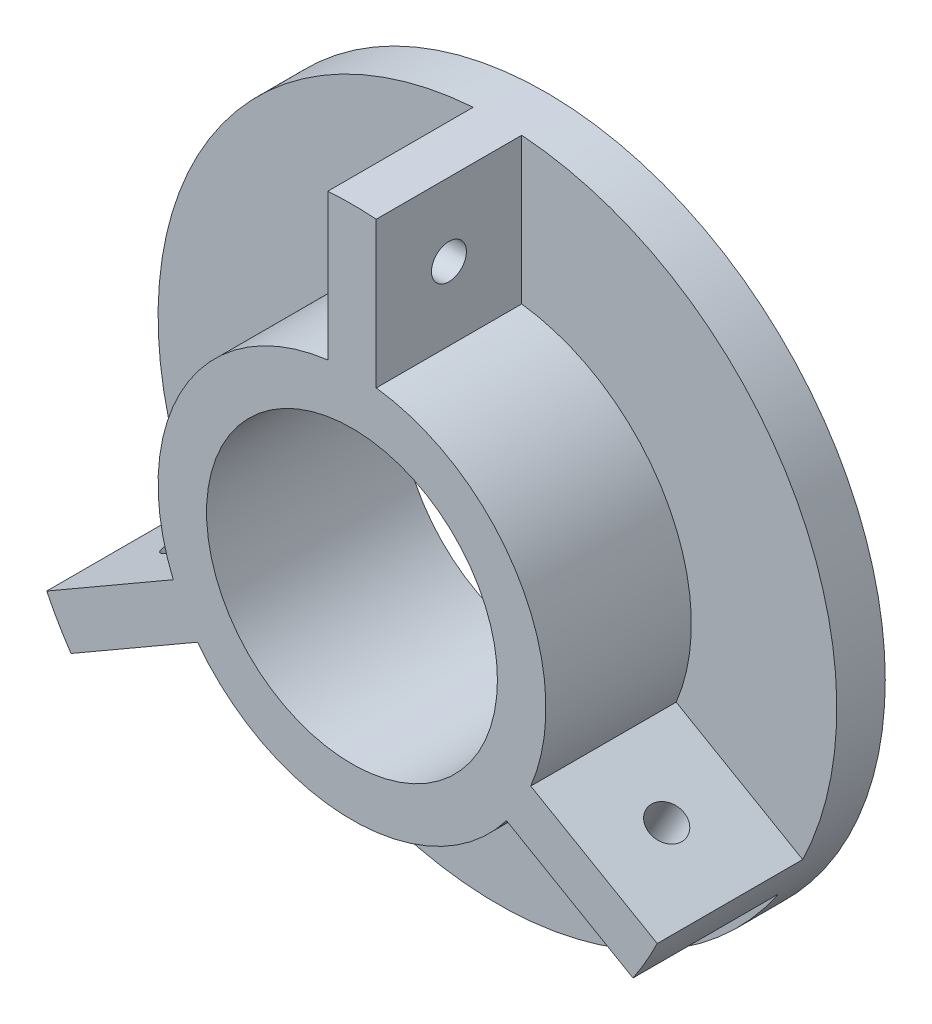
SolidWorks part; units mm, degrees
ref_plane "Front Plane" through (0, 0, 0) normal (0, 0, 1) x (1, 0, 0)
ref_plane "Top Plane" through (0, 0, 0) normal (0, 1, 0) x (1, 0, 0)
ref_plane "Right Plane" through (0, 0, 0) normal (1, 0, 0) x (0, 0, -1)
sketch "Sketch2" plane through (0, 0, 0) normal (0, 0, 1) x (1, 0, 0)
  circle A0 centre (0, 0) radius 15
  circle A1 centre (0, 0) radius 35
  dimension "D1" = 30
  dimension "D2" = 20
extrude "Boss-Extrude1" add sketch "Sketch2" along normal blind 5
sketch "Sketch3" plane through (0, 0, 5) normal (0, 0, 1) x (1, 0, 0)
  line L0 (0, 19.999) -> (0, 35) construction
  line L1 (15.9338, -12.0861) -> (28.9835, -19.6204)
  line L2 (-2.5, 19.8421) -> (2.5, 19.8421) construction
  line L3 (-2.5, 19.8421) -> (-2.5, 34.9106)
  line L4 (-2.5, 34.9106) -> (2.5, 34.9106) construction
  line L5 (2.5, 19.8421) -> (2.5, 34.9106)
  line L6 (18.4338, -7.756) -> (31.4835, -15.2902)
  line L7 (-18.4338, -7.756) -> (-31.4835, -15.2902)
  line L8 (-15.9338, -12.0861) -> (-28.9835, -19.6204)
  circle A0 centre (0, 0) radius 14.999
  circle A1 centre (0, 0) radius 19.999
  circle A2 centre (0, 0) radius 35 construction
  arc A3 (-2.5, 34.9106) -> (2.5, 34.9106) centre (0, 0) cw
  arc A4 (31.4835, -15.2902) -> (28.9835, -19.6204) centre (0, 0) cw
  arc A5 (-28.9835, -19.6204) -> (-31.4835, -15.2902) centre (0, 0) cw
  point P14 (0, 34.9106)
  point P26 (0, 0)
  circle M4 centre (0, 0) radius 35
  circle M5 centre (0, 0) radius 15
  dimension "D2" = 5
  dimension "D1" = 5
  dimension "D3" = 3
extrude "Boss-Extrude3" add sketch "Sketch3" along normal blind 15 contours A1 M5 | A1 L5 L3 M4 | A1 L1 L6 M4 | A1 L7 L8 M4
sketch "Sketch4" plane through (2.5, 0, 0) normal (1, 0, 0) x (0, 0, -1)
  circle A0 centre (-12.5, 27.3764) radius 1.8
  dimension "D1" = 3.6
extrude "Cut-Extrude1" cut sketch "Sketch4" against normal up to next
pattern_circular "CirPattern1" count 3 over 360 about axis through (0, 0, 5) along (0, 0, -1) of "Cut-Extrude1"
